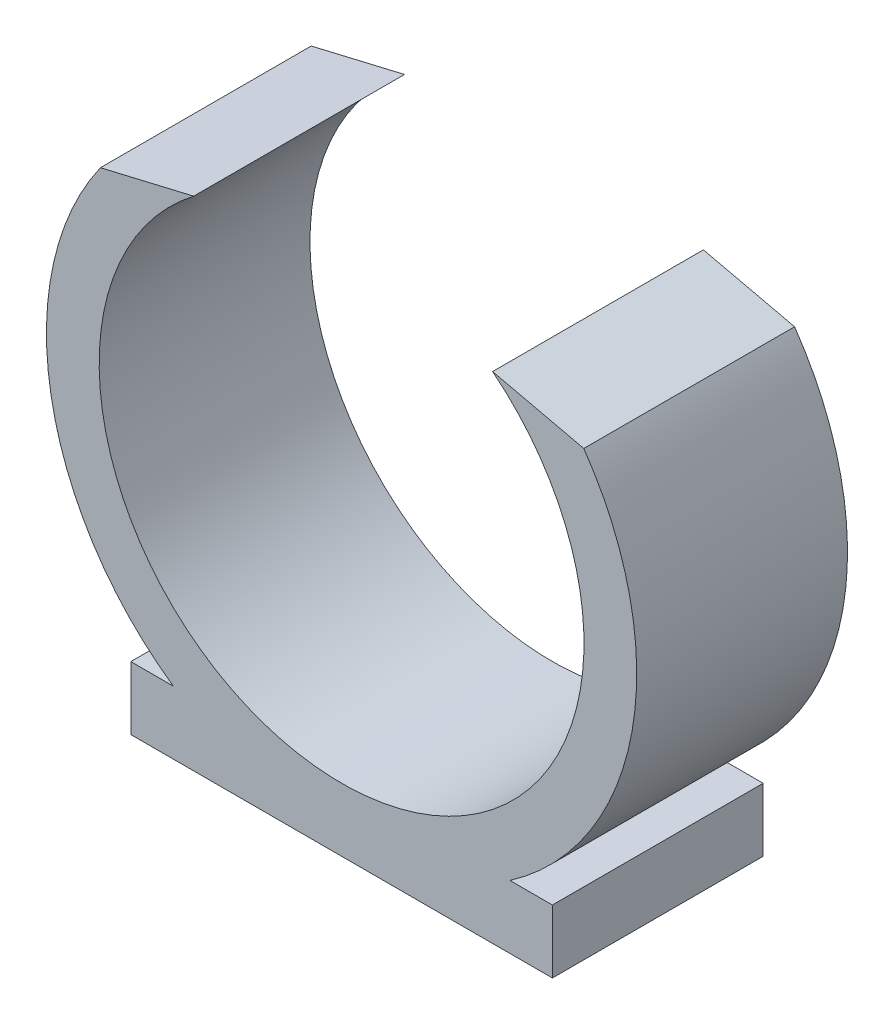
SolidWorks part; units mm, degrees
ref_plane "前视基准面" through (0, 0, 0) normal (0, 0, 1) x (1, 0, 0)
ref_plane "上视基准面" through (0, 0, 0) normal (0, 1, 0) x (1, 0, 0)
ref_plane "右视基准面" through (0, 0, 0) normal (1, 0, 0) x (0, 0, -1)
other "Configuration Table"
sketch "草图1" plane through (0, 0, 0) normal (0, 0, 1) x (1, 0, 0)
  line L0 (8.9922, 1.5) -> (10, 1.5)
  line L1 (0, 0) -> (10, 0)
  line L2 (0, 0) -> (0, 1.5)
  line L3 (0, 1.5) -> (1.0078, 1.5)
  line L4 (10, 0) -> (10, 1.5)
  line L5 (-0.7206, 11.2842) -> (1.4922, 11.8061)
  line L6 (10.7447, 11.2498) -> (8.5817, 11.7482)
  arc A0 (-0.7206, 11.2842) -> (1.0078, 1.5) centre (5, 7.25) ccw
  arc A1 (1.4922, 11.8061) -> (8.5817, 11.7482) centre (5, 7.25) ccw
  arc A2 (8.9922, 1.5) -> (10.7447, 11.2498) centre (5, 7.25) ccw
  point P6 (1.4922, 11.8061)
  point P7 (8.5817, 11.8061)
  point P8 (5, 0)
  point P15 (10.7447, 11.2498)
  point P16 (-0.7206, 11.2498)
  dimension "D3" = 11.5
  dimension "D4" = 14
  dimension "D1" = 1.5
  dimension "D2" = 10
extrude "凸台-拉伸1" add sketch "草图1" along normal blind 5
